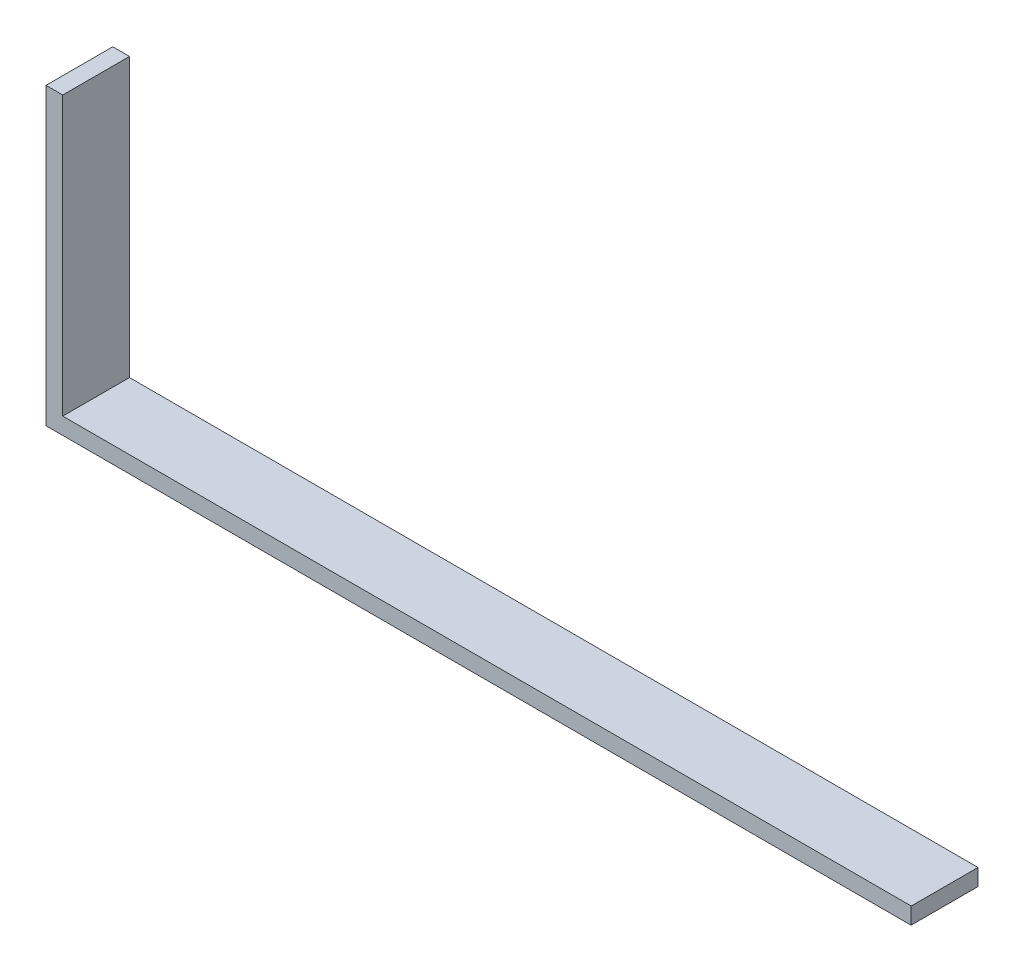
SolidWorks part; units mm, degrees
ref_plane "Alzado" through (0, 0, 0) normal (0, 0, 1) x (1, 0, 0)
ref_plane "Planta" through (0, 0, 0) normal (0, 1, 0) x (1, 0, 0)
ref_plane "Vista lateral" through (0, 0, 0) normal (1, 0, 0) x (0, 0, -1)
sketch "Croquis1" plane through (0, 0, 0) normal (0, 0, 1) x (1, 0, 0)
  line L0 (645.545, -211.585) -> (645.445, -224.305)
  line L1 (645.445, -224.305) -> (-12.72, -224.305)
  line L2 (-12.72, -224.305) -> (-12.72, 0)
  line L3 (-12.72, 0) -> (0, 0)
  line L4 (0, 0) -> (0, -211.585)
  line L5 (0, -211.585) -> (645.545, -211.585)
  dimension "D1" = 658.165
  dimension "D2" = 224.305
  dimension "D3" = 12.72
  dimension "D4" = 12.72
extrude "Saliente-Extruir1" add sketch "Croquis1" along normal blind 50.8
